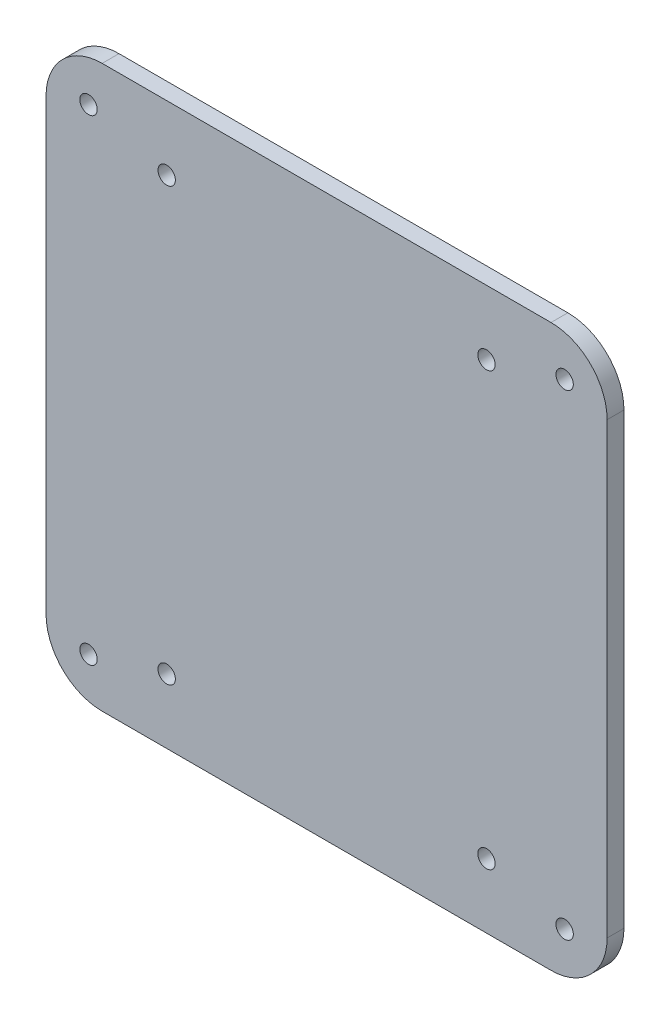
SolidWorks part; units mm, degrees
ref_plane "前视基准面" through (0, 0, 0) normal (0, 0, 1) x (1, 0, 0)
ref_plane "上视基准面" through (0, 0, 0) normal (0, 1, 0) x (1, 0, 0)
ref_plane "右视基准面" through (0, 0, 0) normal (1, 0, 0) x (0, 0, -1)
sketch "草图1" plane through (0, 0, 0) normal (0, 0, 1) x (1, 0, 0)
  line L0 (0, 50) -> (0, -50) construction
  line L5 (-40, -50) -> (40, -50)
  line L6 (-50, -40) -> (-50, 40)
  line L7 (-40, 50) -> (40, 50)
  line L8 (50, -40) -> (50, 40)
  line L9 (-50, -50) -> (50, 50) construction
  line L10 (-50, 50) -> (50, -50) construction
  line L11 (-50, 0) -> (50, 0) construction
  circle A0 centre (-28.5, 38.5) radius 1.55
  circle A1 centre (28.5, 38.5) radius 1.55
  circle A2 centre (28.5, -38.5) radius 1.55
  circle A3 centre (-28.5, -38.5) radius 1.55
  arc A4 (40, 50) -> (50, 40) centre (40, 40) cw
  arc A5 (40, -50) -> (50, -40) centre (40, -40) ccw
  arc A6 (-40, -50) -> (-50, -40) centre (-40, -40) cw
  arc A7 (-50, 40) -> (-40, 50) centre (-40, 40) cw
  circle A8 centre (-42.4264, 42.4264) radius 1.55
  circle A12 centre (42.4264, 42.4264) radius 1.55
  circle A13 centre (42.4264, -42.4264) radius 1.55
  circle A14 centre (-42.4264, -42.4264) radius 1.55
  point P0 (0, 0)
  point P10 (0, 0)
  dimension "D3" = 100
  dimension "D5" = 10
  dimension "D6" = 60
  dimension "D1" = 57
  dimension "D2" = 77
  dimension "D4" = 100
  dimension "D7" = 28.5
  dimension "D8" = 38.5
  dimension "D9" = 38.5
  dimension "D10" = 28.5
  dimension "D11" = 28.5
  dimension "D12" = 38.5
extrude "凸台-拉伸1" add sketch "草图1" along normal blind 3
